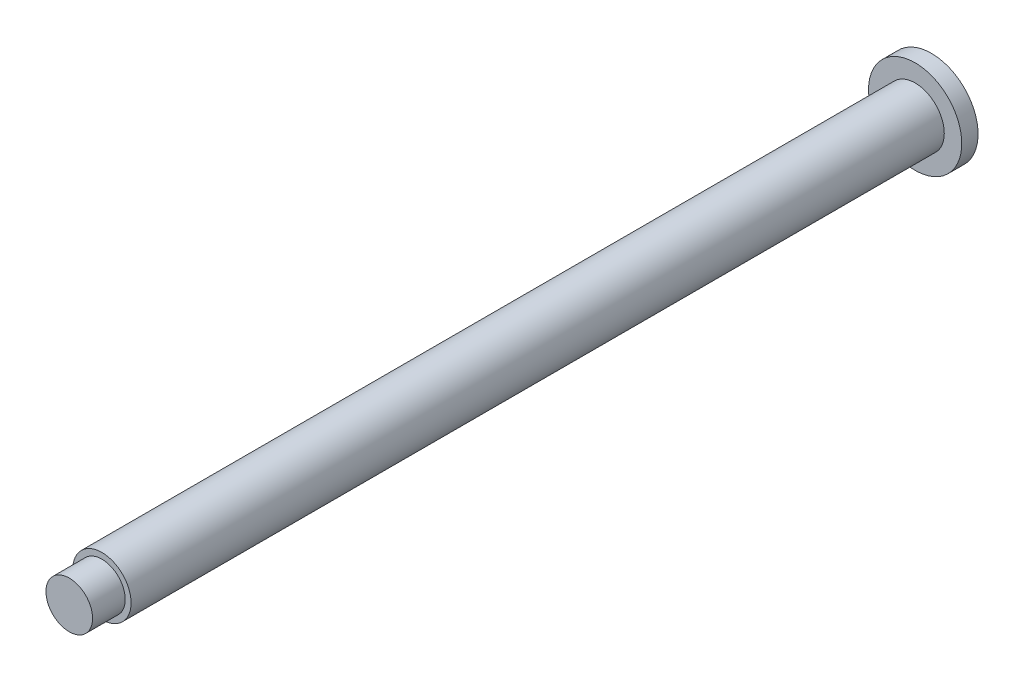
SolidWorks part; units mm, degrees
ref_plane "Front Plane" through (0, 0, 0) normal (1, 0, 0) x (0, 1, 0)
ref_plane "Top Plane" through (0, 0, 0) normal (0, 0, 1) x (0, 1, 0)
ref_plane "Right Plane" through (0, 0, 0) normal (0, 1, 0) x (-1, 0, 0)
sketch "Sketch1" plane through (0, 0, 0) normal (0, 0, 1) x (0, 1, 0)
  circle A0 centre (0, 0) radius 2.5
  dimension "D1" = 5
extrude "Boss-Extrude1" add sketch "Sketch1" along normal blind 69.75 contours A0
sketch "Sketch2" plane through (0, 0, 0) normal (0, 0, -1) x (1, 0, 0)
  circle A0 centre (0, 0) radius 4
  dimension "D1" = 8
extrude "Boss-Extrude2" add sketch "Sketch2" along normal blind 1.4
sketch "Sketch3" plane through (0, 0, -1.4) normal (0, 0, -1) x (1, 0, 0)
  circle A0 centre (0, 0) radius 2.05
  dimension "D1" = 4.1
extrude "Cut-Extrude1" cut sketch "Sketch3" against normal blind 3
sketch "Sketch4" plane through (0, 0, 69.75) normal (0, 0, 1) x (1, 0, 0)
  circle A0 centre (0, 0) radius 2
  dimension "D1" = 4
extrude "Boss-Extrude3" add sketch "Sketch4" along normal blind 2.8
equation "\"whitekey_cutout_length\"= 101.5"
equation "\"key_mount_recess_length\"=50"
equation "\"key_mount_recess_height\"=12.5"
equation "\"key_mount_recess_depth\"=1.5"
equation "\"wall_thickness\"=10"
equation "\"guide_brace_height\"=20"
equation "\"guide_brace_thickness\"=2"
equation "\"dowel_recess_depth\"=10"
equation "\"dowel_recess_offset\"=3.25"
equation "\"base_mount_height\"=40"
equation "\"base_rear_length\"=80"
equation "\"base_front_length\"=111.5"
equation "\"screw_hole_wall_offset\"=7.25"
equation "\"screw_hole_edge_inset\"=\"dowel_recess_depth\"/2"
equation "\"screw_hole_diameter\"=3.8"
equation "\"screw_head_hole_diameter\"=6.7"
equation "\"screw_nut_hole_side_len\"=3.5"
equation "\"screw_nut_recess_offset\"=0.35"
equation "\"screw_head_and_nut_recess_depth\"=2.5"
equation "\"screw_shaft_diameter\"=3.5"
equation "\"switch_board_width\"=30"
equation "\"switch_board_wall_offset\"=11.5"
equation "\"heatset_insert_hole_diameter\"=4.8"
equation "\"heatset_insert_hole_depth\"=3.8"
equation "\"front_rear_panel_width\"=23.75"
equation "\"rod_length_adj\"=0.5"
equation "\"rod_insert_length\"=2.8"
equation "\"D1@Boss-Extrude3\"=\"rod_insert_length\""
equation "\"D1@Boss-Extrude2\"=2-\"rod_length_adj\"-0.1"
equation "\"D1@Boss-Extrude1\"=\"rod_length_adj\"+69.25mm"
equation "\"switch_board_thickness\"=1.6"
equation "\"rod_diameter\"=5"
equation "\"rod_head_diameter\"=8"
equation "\"switch_black_key_mount_height\"=8"
equation "\"switch_white_key_mount_height\"=3"
equation "\"D1@Sketch1\"=\"rod_diameter\""
equation "\"D1@Sketch2\"=\"rod_head_diameter\""
equation "\"D1@Sketch3\"=\"rod_diameter\"-1+0.1"
equation "\"D1@Sketch4\"=\"rod_diameter\"-1"
